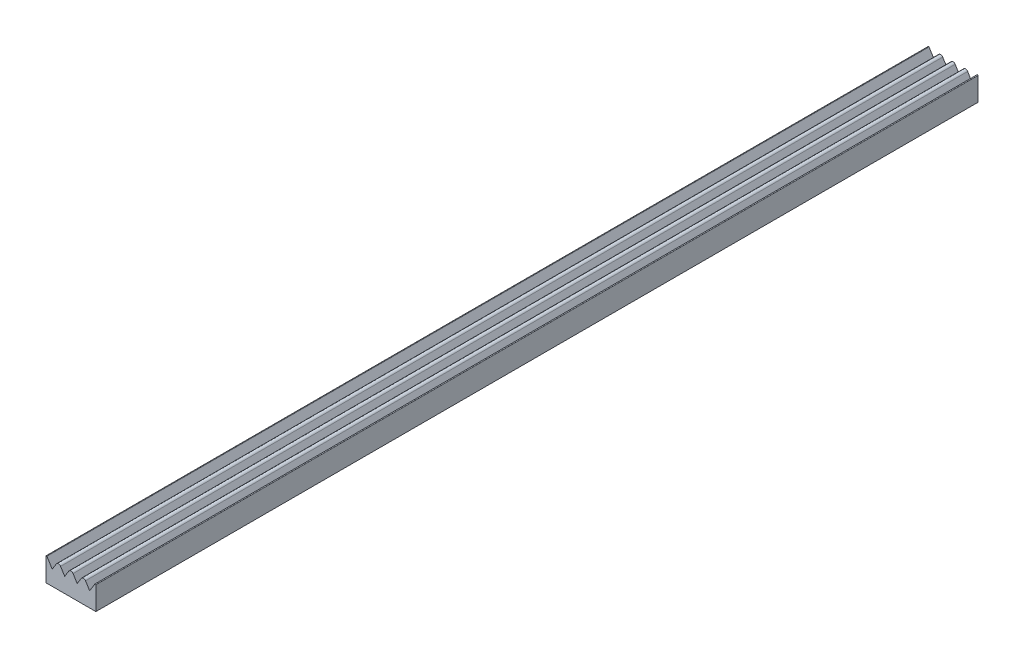
SolidWorks part; units mm, degrees
material "Polyurethane Foam Flexible"
ref_plane "Front Plane" through (0, 0, 0) normal (0, 0, 1) x (1, 0, 0)
ref_plane "Top Plane" through (0, 0, 0) normal (0, 1, 0) x (1, 0, 0)
ref_plane "Right Plane" through (0, 0, 0) normal (1, 0, 0) x (0, 0, -1)
sketch "Sketch1" plane through (0, 0, 0) normal (0, 0, 1) x (1, 0, 0)
  line L0 (-12.7, 6.35) -> (0, 6.35) construction
  line L1 (0, 0) -> (-12.7, 0)
  line L2 (0, 0) -> (0, 5.9072)
  line L3 (-6.35, 0) -> (-6.35, 6.35) construction
  line L4 (-12.7, 0) -> (-12.7, 5.9072)
  line L5 (-12.7, 3.81) -> (0, 3.81) construction
  line L6 (-7.9375, 3.81) -> (-6.8885, 5.4884)
  line L7 (-7.9375, 3.81) -> (-8.9865, 5.4884)
  line L8 (-10.0635, 5.4884) -> (-11.1125, 3.81)
  line L9 (-11.1125, 3.81) -> (-12.4653, 5.9745)
  line L10 (-4.7625, 3.81) -> (-5.8115, 5.4884)
  line L11 (-4.7625, 3.81) -> (-3.7135, 5.4884)
  line L14 (-2.6365, 5.4884) -> (-1.5875, 3.81)
  line L15 (-1.5875, 3.81) -> (-0.2347, 5.9745)
  arc A0 (-3.7135, 5.4884) -> (-2.6365, 5.4884) centre (-3.175, 5.1519) cw
  arc A1 (-6.8885, 5.4884) -> (-5.8115, 5.4884) centre (-6.35, 5.1519) cw
  arc A2 (-8.9865, 5.4884) -> (-10.0635, 5.4884) centre (-9.525, 5.1519) ccw
  arc A3 (0, 5.9072) -> (-0.2347, 5.9745) centre (-0.127, 5.9072) ccw
  arc A4 (-12.4653, 5.9745) -> (-12.7, 5.9072) centre (-12.573, 5.9072) ccw
  dimension "D7" = 0.635
  dimension "D8" = 0.127
  dimension "D1" = 6.35
  dimension "D2" = 12.7
  dimension "D3" = 1.5875
  dimension "D4" = 2.54
  dimension "D5" = 1.5875
extrude "Boss-Extrude1" add sketch "Sketch1" along normal blind 224.6312
